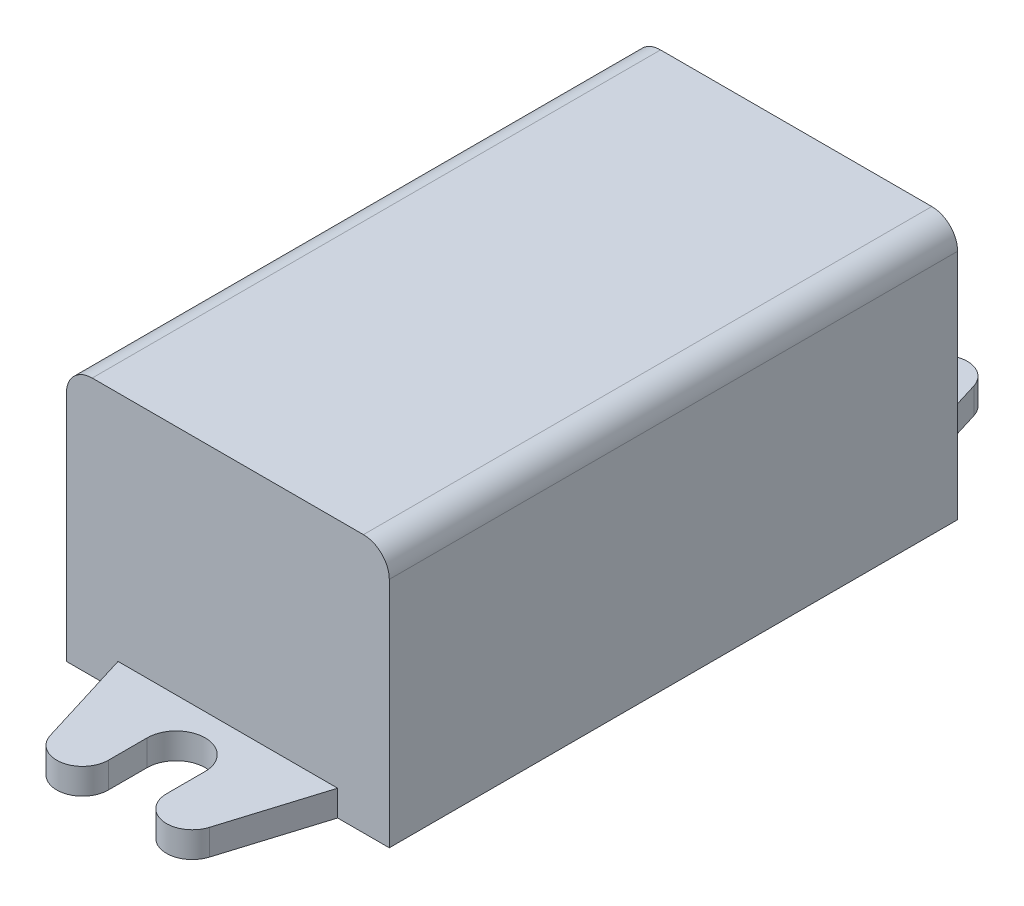
SolidWorks part; units mm, degrees
ref_plane "前视基准面" through (0, 0, 0) normal (0, 0, 1) x (1, 0, 0)
ref_plane "上视基准面" through (0, 0, 0) normal (0, 1, 0) x (1, 0, 0)
ref_plane "右视基准面" through (0, 0, 0) normal (1, 0, 0) x (0, 0, -1)
sketch "草图1" plane through (0, 0, 0) normal (0, 0, 1) x (1, 0, 0)
  line L1 (-12.5, 10) -> (12.5, 10)
  line L2 (-12.5, 10) -> (-12.5, -10)
  line L3 (-12.5, -10) -> (12.5, -10)
  line L4 (12.5, 10) -> (12.5, -10)
  line L5 (0, -10) -> (0, 10) construction
  line L6 (-12.5, 0) -> (12.5, 0) construction
  point P0 (0, 0)
  dimension "D1" = 20
  dimension "D2" = 25
extrude "凸台-拉伸1" add sketch "草图1" along normal mid plane 44
sketch "草图2" plane through (0, -10, 0) normal (0, -1, 0) x (1, 0, 0)
  line L0 (0, 37.3746) -> (0, -37.6018) construction
  line L1 (-8.5, -22) -> (-6.1613, -29.589)
  line L2 (-12.5, -22) -> (12.5, -22) construction
  line L3 (-2.25, -29) -> (-2.25, -26)
  line L4 (-12.5, 22) -> (-12.5, -22) construction
  line L5 (2.25, -29) -> (2.25, -26)
  line L6 (8.5, -22) -> (6.1613, -29.589)
  line L7 (-8.5, -22) -> (8.5, -22)
  line L8 (-18.9301, 0) -> (23.3046, 0) construction
  line L9 (-8.5, 22) -> (8.5, 22)
  line L10 (8.5, 22) -> (6.1613, 29.589)
  line L11 (2.25, 29) -> (2.25, 26)
  line L12 (-2.25, 29) -> (-2.25, 26)
  line L13 (-8.5, 22) -> (-6.1613, 29.589)
  arc A0 (-6.1613, -29.589) -> (-2.25, -29) centre (-4.25, -29) ccw
  arc A1 (-2.25, -26) -> (2.25, -26) centre (0, -26) cw
  arc A2 (6.1613, -29.589) -> (2.25, -29) centre (4.25, -29) cw
  arc A3 (6.1613, 29.589) -> (2.25, 29) centre (4.25, 29) ccw
  arc A4 (-2.25, 26) -> (2.25, 26) centre (0, 26) ccw
  arc A5 (-6.1613, 29.589) -> (-2.25, 29) centre (-4.25, 29) cw
  dimension "D1" = 4.5
  dimension "D5" = 2
  dimension "D2" = 7
  dimension "D3" = 3
  dimension "D4" = 4
extrude "凸台-拉伸2" add sketch "草图2" against normal blind 2
fillet "圆角1" radius 2 2 edges at (-12.5, 10, 0) (12.5, 10, 0)
